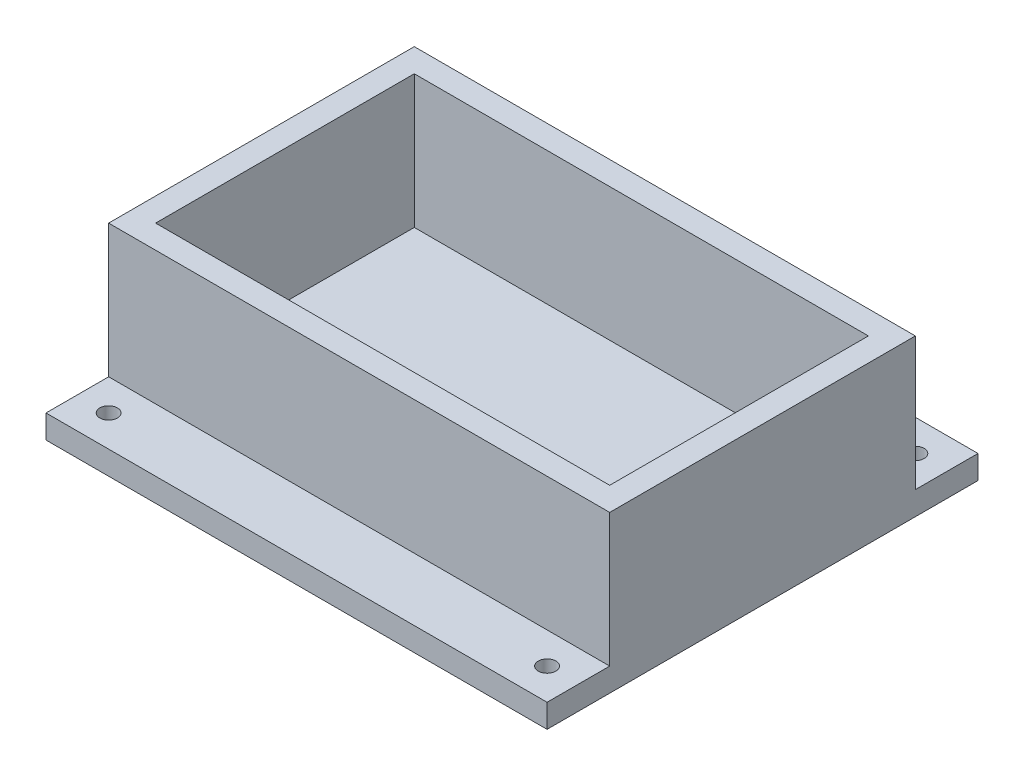
SolidWorks part; units mm, degrees
material "6061-T6 (SS)"
ref_plane "Front Plane" through (0, 0, 0) normal (0, 0, 1) x (1, 0, 0)
ref_plane "Top Plane" through (0, 0, 0) normal (0, 1, 0) x (1, 0, 0)
ref_plane "Right Plane" through (0, 0, 0) normal (1, 0, 0) x (0, 0, -1)
sketch "Sketch2" plane through (0, 0, 0) normal (0, 1, 0) x (1, 0, 0)
  line L1 (101.6, -61.976) -> (-101.6, -61.976)
  line L2 (101.6, -61.976) -> (101.6, 61.976)
  line L3 (101.6, 61.976) -> (-101.6, 61.976)
  line L4 (-101.6, -61.976) -> (-101.6, 61.976)
  line L5 (101.6, -61.976) -> (-101.6, 61.976) construction
  line L6 (101.6, 61.976) -> (-101.6, -61.976) construction
  point P0 (0, 0)
  dimension "D1" = 203.2
  dimension "D2" = 123.952
extrude "Main Block" add sketch "Sketch2" along normal blind 63.5
shell "Shell" thickness 9.525
sketch "Sketch6" plane through (0, 9.525, 0) normal (0, 1, 0) x (1, 0, 0)
  line L1 (-101.6, 61.976) -> (101.6, 61.976)
  line L2 (-101.6, 61.976) -> (-101.6, 87.376)
  line L3 (-101.6, 87.376) -> (101.6, 87.376)
  line L4 (101.6, 61.976) -> (101.6, 87.376)
  line L5 (-101.6, -61.976) -> (101.6, -61.976)
  line L6 (-101.6, -61.976) -> (-101.6, -87.376)
  line L7 (-101.6, -87.376) -> (101.6, -87.376)
  line L8 (101.6, -61.976) -> (101.6, -87.376)
  circle A0 centre (-88.9, 74.676) radius 3.5687
  circle A1 centre (88.9, 74.676) radius 3.5687
  circle A2 centre (88.9, -74.676) radius 3.5687
  circle A3 centre (-88.9, -74.676) radius 3.5687
  dimension "D5" = 7.1374
  dimension "D6" = 7.1374
  dimension "D7" = 7.1374
  dimension "D8" = 7.1374
  dimension "D1" = 25.4
  dimension "D2" = 203.2
  dimension "D3" = 25.4
  dimension "D4" = 203.2
  dimension "D9" = 12.7
  dimension "D10" = 12.7
  dimension "D11" = 12.7
  dimension "D12" = 12.7
  dimension "D13" = 12.7
  dimension "D14" = 12.7
  dimension "D15" = 12.7
  dimension "D16" = 12.7
extrude "Mounting Flanges" add sketch "Sketch6" against normal blind 9.525
